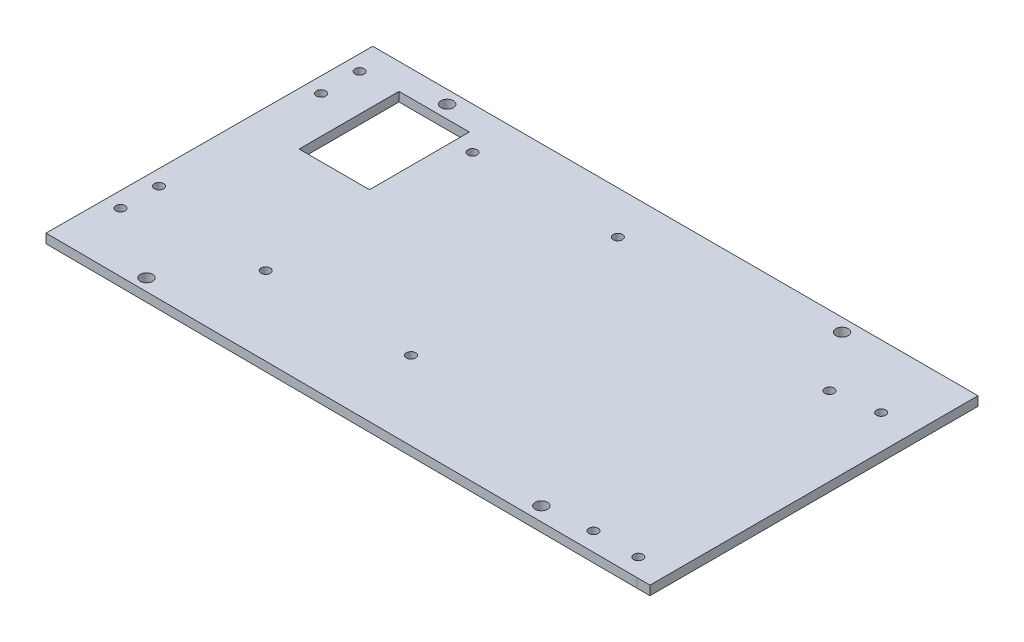
SolidWorks part; units mm, degrees
ref_plane "Front Plane" through (0, 0, 0) normal (0, 0, 1) x (1, 0, 0)
ref_plane "Top Plane" through (0, 0, 0) normal (0, 1, 0) x (1, 0, 0)
ref_plane "Right Plane" through (0, 0, 0) normal (1, 0, 0) x (0, 0, -1)
sketch "Sketch1" plane through (0, 0, 0) normal (0, 1, 0) x (1, 0, 0)
  line L2 (-84.4586, 48.7726) -> (-94.4584, 48.8206)
  line L3 (-94.4584, 48.8206) -> (-94.5786, 23.8209)
  line L18 (-94.953, -54.0782) -> (98.3617, -55.0073)
  line L24 (102.5861, 22.8733) -> (102.6438, 34.8732)
  line L31 (-94.4584, 48.8206) -> (-94.953, -54.0782)
  line L32 (98.3617, -55.0073) -> (102.5861, -55.0073)
  line L33 (102.5861, -55.0073) -> (102.5861, 48.7726)
  line L34 (102.5861, 48.7726) -> (-84.4586, 48.7726)
  line L35 (-94.4584, 48.8206) -> (-94.8814, -39.1783)
  line L37 (-84.4586, 48.7726) -> (-62.6656, 48.7726)
  line L38 (-84.4586, 48.7726) -> (-84.4586, 26.834)
  line L39 (-84.4586, 26.834) -> (-62.6656, 26.834)
  line L40 (-62.6656, 48.7726) -> (-62.6656, 26.834)
  circle A0 centre (-89.5486, 30.0468) radius 1.5
  circle A1 centre (-89.4885, 42.5467) radius 1.5
  circle A2 centre (-89.7913, -22.4526) radius 1.5
  circle A3 centre (-89.8514, -34.9525) radius 1.5
  circle A4 centre (-1.07, -29.1291) radius 1.5
  circle A5 centre (-48.619, -28.9006) radius 1.5
  circle A6 centre (77.0152, 28.9963) radius 1.5
  circle A7 centre (91.5762, 31.2402) radius 1.5
  circle A8 centre (-0.748, 37.8701) radius 1.5
  circle A9 centre (-48.297, 38.0987) radius 1.5
  circle A10 centre (78.1095, -48.9099) radius 1.5
  circle A11 centre (92.7574, -48.9803) radius 1.5
extrude "Boss-Extrude1" add sketch "Sketch1" along normal blind 3 contours L34 L40 L39 L38 L2 L3 L31 L18 L32 L33 A11 A10 A9 A8 A7 A6 A5 A4 A3 A2 A1 A0
sketch "Sketch3" plane through (0, 3, 0) normal (0, 1, 0) x (1, 0, 0)
  line L0 (-94.4584, 48.8206) -> (-77.4584, 48.8206)
  line L2 (-77.4584, 48.8206) -> (-54.5487, 48.8206)
  line L3 (-77.4584, 48.8206) -> (-77.4584, 10.8206)
  line L4 (-77.4584, 10.8206) -> (-54.5487, 10.8206)
  line L5 (-54.5487, 48.8206) -> (-54.5487, 10.8206)
  line M14 (102.5861, 48.7726) -> (-62.6656, 48.7726)
  line M15 (-62.6656, 48.7726) -> (-62.6656, 26.834)
  line M16 (-62.6656, 26.834) -> (-84.4586, 26.834)
extrude "Cut-Extrude1" cut sketch "Sketch3" against normal through all both contours L5 L3 L4 M14 M15 M16
sketch "Sketch4" plane through (0, 0, 0) normal (0, -1, 0) x (1, 0, 0)
  line L0 (-54.5487, -48.7726) -> (-54.5487, -10.8206) construction
  line L1 (-84.4586, -26.834) -> (-77.4584, -26.834)
  line L4 (-77.4584, -26.834) -> (-77.4584, -43.3336)
  line L7 (-77.4584, -43.3336) -> (-54.5487, -43.3336)
  line L10 (-84.4586, -48.7726) -> (-84.4586, -26.834) construction
  line L11 (102.5861, -48.7726) -> (-54.5487, -48.7726) construction
  line L12 (-84.4586, -48.7726) -> (-94.4584, -48.8206) construction
  line L13 (-84.4586, -48.7726) -> (-84.4586, -26.834)
  line L14 (102.5861, -48.7726) -> (-54.5487, -48.7726)
  line L15 (-84.4586, -48.7726) -> (-94.4584, -48.8206)
  line L16 (-84.4586, -48.7726) -> (-54.5487, -48.7726)
  line M17 (-54.5487, -10.8206) -> (-54.5487, -48.7726)
  line M24 (-84.4586, -48.7726) -> (-84.4586, -26.834)
  line M25 (-84.4586, -26.834) -> (-77.4584, -26.834)
extrude "Boss-Extrude4" add sketch "Sketch4" against normal blind 3 contours L16 L7 L4 M24 M17 M25
sketch "Sketch5" plane through (0, 0, 0) normal (0, -1, 0) x (1, 0, 0)
  line L1 (102.5861, -48.7726) -> (-94.4584, -48.7726)
  line L2 (102.5861, -48.7726) -> (102.5861, -51.7726)
  line L3 (102.5861, -51.7726) -> (-94.4584, -51.7726)
  line L4 (-94.4584, -48.7726) -> (-94.4584, -51.7726)
extrude "Boss-Extrude5" add sketch "Sketch5" against normal blind 3
sketch "Sketch6" plane through (0, 0, 0) normal (0, -1, 0) x (1, 0, 0)
  line L0 (1.7044, 1.3851) -> (34.005, 1.3851)
  line L2 (-94.4584, -51.7726) -> (102.5861, -51.7726) construction
  line L3 (1.7044, 54.5427) -> (1.7044, -51.7726)
  line L4 (-94.953, 54.0782) -> (98.3617, 55.0073) construction
  circle A0 centre (-66.0036, -47.5531) radius 2
  circle A2 centre (62.5486, -47.5531) radius 2
  circle A3 centre (62.5486, 50.3232) radius 2
  circle A4 centre (-66.0036, 50.3232) radius 2
extrude "Cut-Extrude3" cut sketch "Sketch6" against normal through all both contours A4 | A3 | A2 | A0
